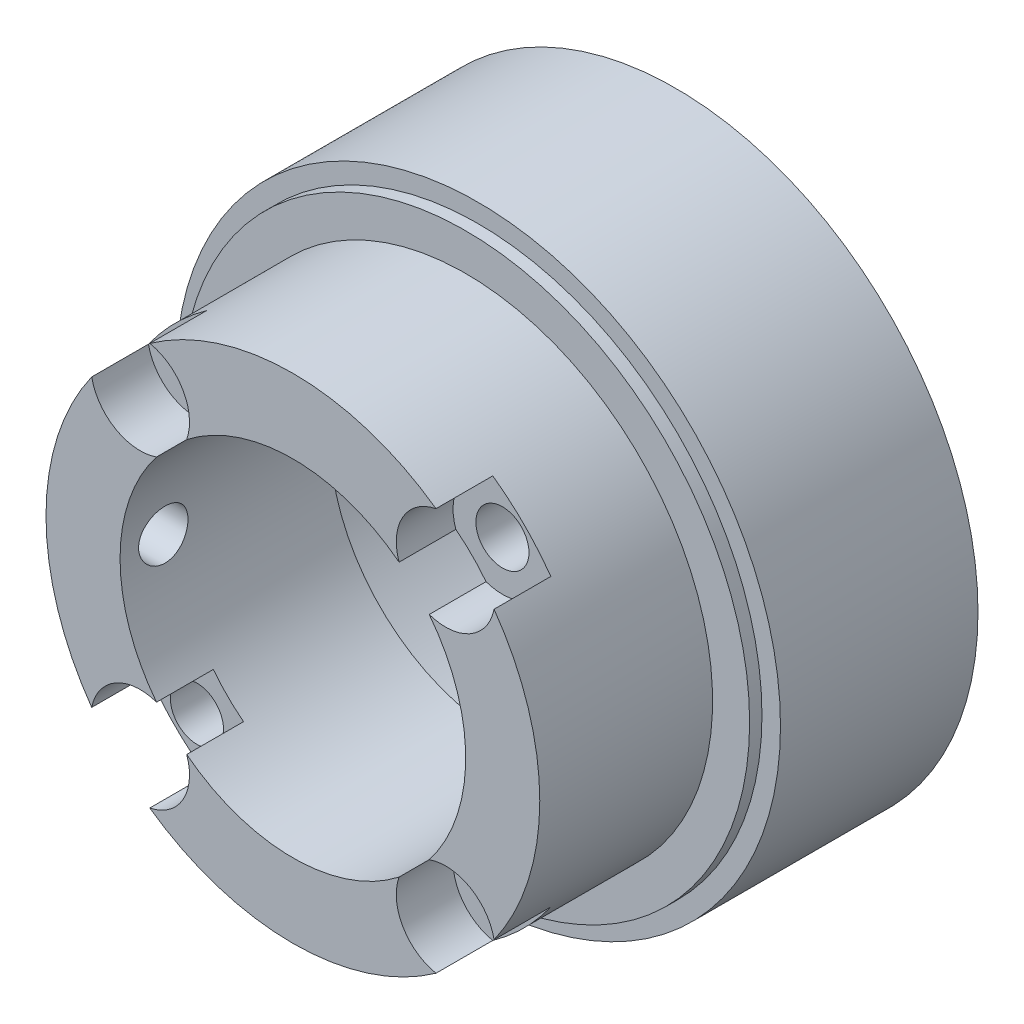
SolidWorks part; units mm, degrees
material "普通碳钢"
ref_plane "前视基准面" through (0, 0, 0) normal (0, 0, 1) x (1, 0, 0)
ref_plane "上视基准面" through (0, 0, 0) normal (0, 1, 0) x (1, 0, 0)
ref_plane "右视基准面" through (0, 0, 0) normal (1, 0, 0) x (0, 0, -1)
sketch "草图1" plane through (0, 0, 0) normal (0, 0, 1) x (1, 0, 0)
  circle A0 centre (0, 0) radius 20
  circle A1 centre (0, 0) radius 14
  dimension "D1" = 40
  dimension "D2" = 28
extrude "凸台-拉伸1" add sketch "草图1" along normal blind 14
sketch "草图2" plane through (0, 0, 0) normal (0, 0, -1) x (-1, 0, 0)
  circle A0 centre (0, 0) radius 24.5
  circle A1 centre (0, 0) radius 14
  dimension "D1" = 49
  dimension "D2" = 28
extrude "凸台-拉伸2" add sketch "草图2" along normal blind 3
sketch "草图3" plane through (0, 0, -3) normal (0, 0, -1) x (-1, 0, 0)
  circle A0 centre (0, 0) radius 21
  circle A1 centre (0, 0) radius 24.5
  dimension "D1" = 49
  dimension "D2" = 42
extrude "凸台-拉伸3" add sketch "草图3" along normal blind 14
hole_wizard "打孔尺寸根据内六角圆柱头螺钉的类型1" positions "草图11" profile "草图12" counterbore size "M4" standard "GB" end condition through all
sketch "草图11" plane through (0, 0, 14) normal (0, 0, 1) x (1, 0, 0)
  line L0 (0, 0) -> (26.7695, 0) construction
  line L1 (0, 0) -> (21.0433, 21.0433) construction
  line L2 (0, 0) -> (-19.1577, 19.1577) construction
  circle A0 centre (0, 0) radius 17.5 construction
  point P15 (12.3744, -12.3744)
  point P17 (12.3744, 12.3744)
  point P23 (-12.3744, 12.3744)
  point P25 (-12.3744, -12.3744)
  dimension "D1" = 35
  dimension "D2" = 45
sketch "草图12" plane through (12.3744, -12.3744, 14) normal (1, 0, 0) x (0, -1, 0)
  line L0 (0, 0) -> (0, 31)
  line L1 (0, 31) -> (2.15, 31)
  line L3 (2.15, 31) -> (2.15, 4.6)
  line L4 (2.15, 4.6) -> (4, 4.6)
  line L5 (4, 4.6) -> (4, 0)
  line L7 (4, 0) -> (0, 0)
  line L11 (0, -6.35) -> (0, 107.95) construction
  dimension "通孔孔直径" = 4.3
  dimension "通孔孔深度" = 31
  dimension "柱形沉头孔直径" = 8
  dimension "柱形沉头孔深度" = 4.6
sketch "草图6" plane through (0, 0, 0) normal (0, 0, 1) x (1, 0, 0)
  circle A0 centre (0, 0) radius 23
  circle A1 centre (0, 0) radius 24.5 construction
  circle A2 centre (0, 0) radius 24.5
  dimension "D1" = 46
extrude "切除-拉伸1" cut sketch "草图6" against normal blind 1
ref_plane "基准面2" through (-20, 0, 0) normal (-1, 0, 0) x (0, 0, 1)
sketch "草图14" plane through (-20, 0, 0) normal (-1, 0, 0) x (0, 0, 1)
  line L0 (0, 0) -> (18.5693, 0) construction
  line L1 (14, -11.593) -> (14, 11.593) construction
  circle A0 centre (10.5, 0) radius 2
  dimension "D1" = 4
  dimension "D2" = 3.5
extrude "切除-拉伸2" cut sketch "草图14" against normal up to next
